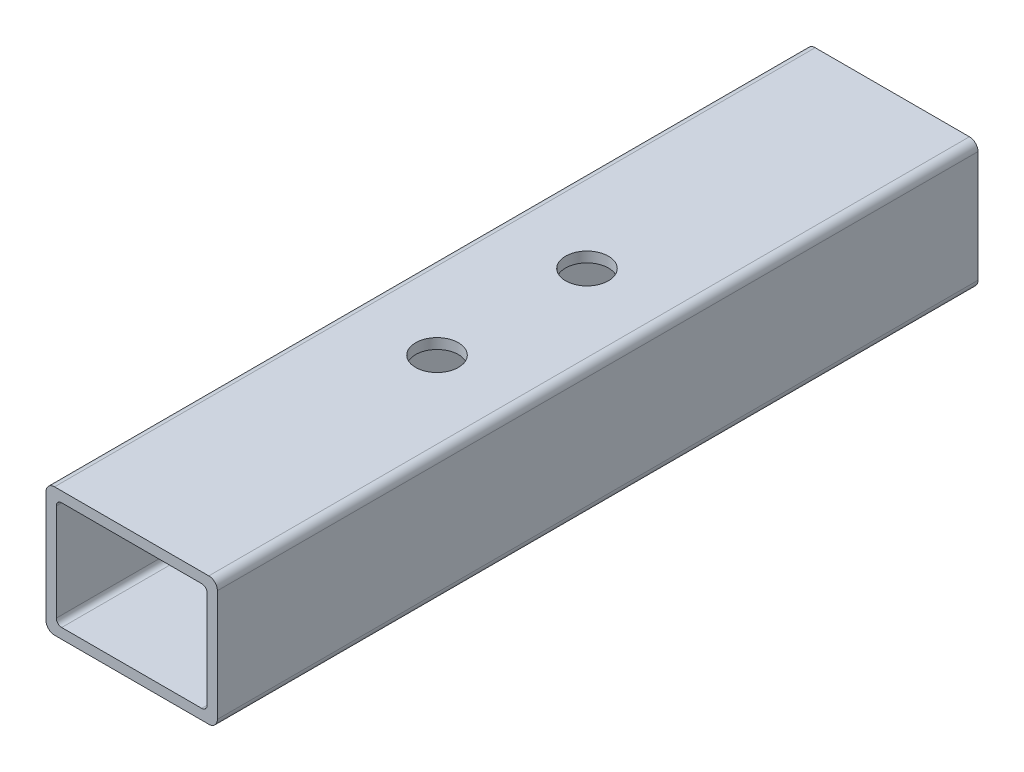
SolidWorks part; units mm, degrees
material "Plain Carbon Steel"
ref_plane "Front" through (0, 0, 0) normal (0, 0, 1) x (1, 0, 0)
ref_plane "Top" through (0, 0, 0) normal (0, 1, 0) x (1, 0, 0)
ref_plane "Right" through (0, 0, 0) normal (1, 0, 0) x (0, 0, -1)
sketch "Sketch1" plane through (0, 0, 0) normal (0, 0, 1) x (1, 0, 0)
  line L0 (-22.352, 0) -> (-25.4, 0) construction
  line L1 (22.86, -19.05) -> (-22.86, -19.05)
  line L2 (25.4, -16.51) -> (25.4, 16.51)
  line L3 (22.86, 19.05) -> (-22.86, 19.05)
  line L4 (-25.4, -16.51) -> (-25.4, 16.51)
  line L5 (25.4, -19.05) -> (-25.4, 19.05) construction
  line L6 (25.4, 19.05) -> (-25.4, -19.05) construction
  line L7 (20.7518, 16.002) -> (-20.7518, 16.002)
  line L8 (22.352, 14.4018) -> (22.352, -14.4018)
  line L9 (20.7518, -16.002) -> (-20.7518, -16.002)
  line L10 (-22.352, 14.4018) -> (-22.352, -14.4018)
  line L11 (22.352, 16.002) -> (-22.352, -16.002) construction
  line L12 (22.352, -16.002) -> (-22.352, 16.002) construction
  line L13 (0, -16.002) -> (0, -19.05) construction
  line L14 (22.352, -14.4018) -> (22.352, -19.05) construction
  line L16 (22.352, -19.05) -> (25.4, -19.05) construction
  arc A0 (-20.7518, -16.002) -> (-22.352, -14.4018) centre (-20.7518, -14.4018) cw
  arc A1 (22.352, -14.4018) -> (20.7518, -16.002) centre (20.7518, -14.4018) cw
  arc A2 (20.7518, 16.002) -> (22.352, 14.4018) centre (20.7518, 14.4018) cw
  arc A3 (-20.7518, 16.002) -> (-22.352, 14.4018) centre (-20.7518, 14.4018) ccw
  arc A4 (22.86, -19.05) -> (25.4, -16.51) centre (22.86, -16.51) ccw
  arc A5 (25.4, 16.51) -> (22.86, 19.05) centre (22.86, 16.51) ccw
  arc A6 (-22.86, 19.05) -> (-25.4, 16.51) centre (-22.86, 16.51) ccw
  arc A7 (-22.86, -19.05) -> (-25.4, -16.51) centre (-22.86, -16.51) cw
  point P0 (0, 0)
  point P6 (0, 0)
  dimension "D2" = 1.6002
  dimension "D3" = 2.54
sketch "Sketch2" plane through (0, 0, 0) normal (1, 0, 0) x (0, 0, -1)
  line L0 (-152.4, 0) -> (152.4, 0) construction
  dimension "Length" = 304.8
ref_plane "Plane1" through (25.4, 0, 0) normal (1, 0, 0) x (0, 0, -1)
sketch "Sketch5" plane through (25.4, 0, 0) normal (1, 0, 0) x (0, 0, -1)
  line L0 (-152.4, 19.05) -> (-152.4, -19.05) construction
  line L1 (152.4, 19.05) -> (152.4, -19.05) construction
sketch "Sketch4" plane through (0, 0, 0) normal (0, 0, 1) x (1, 0, 0)
  line L0 (25.4, -16.51) -> (25.4, 16.51) construction
  line L1 (22.86, 19.05) -> (-22.86, 19.05) construction
  line L2 (-25.4, -16.51) -> (-25.4, 16.51) construction
  line L3 (22.86, -19.05) -> (-22.86, -19.05) construction
  line L4 (22.352, 14.4018) -> (22.352, -14.4018) construction
  line L5 (20.7518, -16.002) -> (-20.7518, -16.002) construction
  line L6 (-22.352, 14.4018) -> (-22.352, -14.4018) construction
  line L7 (20.7518, 16.002) -> (-20.7518, 16.002) construction
  line L8 (25.4, -16.51) -> (25.4, 16.51)
  line L9 (22.86, 19.05) -> (-22.86, 19.05)
  line L10 (-25.4, -16.51) -> (-25.4, 16.51)
  line L11 (22.86, -19.05) -> (-22.86, -19.05)
  line L12 (22.352, 14.4018) -> (22.352, -14.4018)
  line L13 (20.7518, -16.002) -> (-20.7518, -16.002)
  line L14 (-22.352, 14.4018) -> (-22.352, -14.4018)
  line L15 (20.7518, 16.002) -> (-20.7518, 16.002)
  arc A0 (25.4, 16.51) -> (22.86, 19.05) centre (22.86, 16.51) ccw construction
  arc A1 (-22.86, 19.05) -> (-25.4, 16.51) centre (-22.86, 16.51) ccw construction
  arc A2 (-25.4, -16.51) -> (-22.86, -19.05) centre (-22.86, -16.51) ccw construction
  arc A3 (22.86, -19.05) -> (25.4, -16.51) centre (22.86, -16.51) ccw construction
  arc A4 (20.7518, -16.002) -> (22.352, -14.4018) centre (20.7518, -14.4018) ccw construction
  arc A5 (-22.352, -14.4018) -> (-20.7518, -16.002) centre (-20.7518, -14.4018) ccw construction
  arc A6 (-20.7518, 16.002) -> (-22.352, 14.4018) centre (-20.7518, 14.4018) ccw construction
  arc A7 (22.352, 14.4018) -> (20.7518, 16.002) centre (20.7518, 14.4018) ccw construction
  arc A8 (25.4, 16.51) -> (22.86, 19.05) centre (22.86, 16.51) ccw
  arc A9 (-22.86, 19.05) -> (-25.4, 16.51) centre (-22.86, 16.51) ccw
  arc A10 (-25.4, -16.51) -> (-22.86, -19.05) centre (-22.86, -16.51) ccw
  arc A11 (22.86, -19.05) -> (25.4, -16.51) centre (22.86, -16.51) ccw
  arc A12 (20.7518, -16.002) -> (22.352, -14.4018) centre (20.7518, -14.4018) ccw
  arc A13 (-22.352, -14.4018) -> (-20.7518, -16.002) centre (-20.7518, -14.4018) ccw
  arc A14 (-20.7518, 16.002) -> (-22.352, 14.4018) centre (-20.7518, 14.4018) ccw
  arc A15 (22.352, 14.4018) -> (20.7518, 16.002) centre (20.7518, 14.4018) ccw
extrude "Boss-Extrude1" add sketch "Sketch4" along normal blind 225.425
sketch "Sketch6" plane through (0, 19.05, 0) normal (0, 1, 0) x (1, 0, 0)
  line L0 (0, -225.425) -> (0, -182.5625) construction
  line L2 (-22.86, -182.5625) -> (22.86, -182.5625) construction
  line L3 (-22.86, 0) -> (-22.86, -225.425) construction
  line L4 (22.86, 0) -> (22.86, -225.425) construction
  line L5 (-22.86, -42.8625) -> (22.86, -42.8625) construction
  line L6 (22.86, -225.425) -> (-22.86, -225.425) construction
  line L7 (0, -182.5625) -> (0, -42.8625) construction
  line L8 (0, -42.8625) -> (0, 0) construction
  line L9 (22.86, 0) -> (-22.86, 0) construction
  dimension "D1" = 139.7
sketch "Sketch9" plane through (0, 19.05, 0) normal (0, 1, 0) x (1, 0, 0)
  line L0 (0, -225.425) -> (0, -134.9375) construction
  line L1 (22.86, -225.425) -> (-22.86, -225.425) construction
  line L2 (0, -134.9375) -> (0, -90.4875) construction
  line L3 (0, -90.4875) -> (0, 0) construction
  circle A0 centre (0, -134.9375) radius 6.35
  circle A1 centre (0, -90.4875) radius 6.35
  dimension "D2" = 12.7
  dimension "D1" = 44.45
extrude "Cut-Extrude2" cut sketch "Sketch9" along direction (0, -1, 0) on the side against the normal up to next (3.048 mm away)
equation "\"D3@Sketch1\"=\"Outside Width@Sketch1\"*.05"
equation "\"D2@Sketch1\"=\"D1@Sketch1\"*.05"
